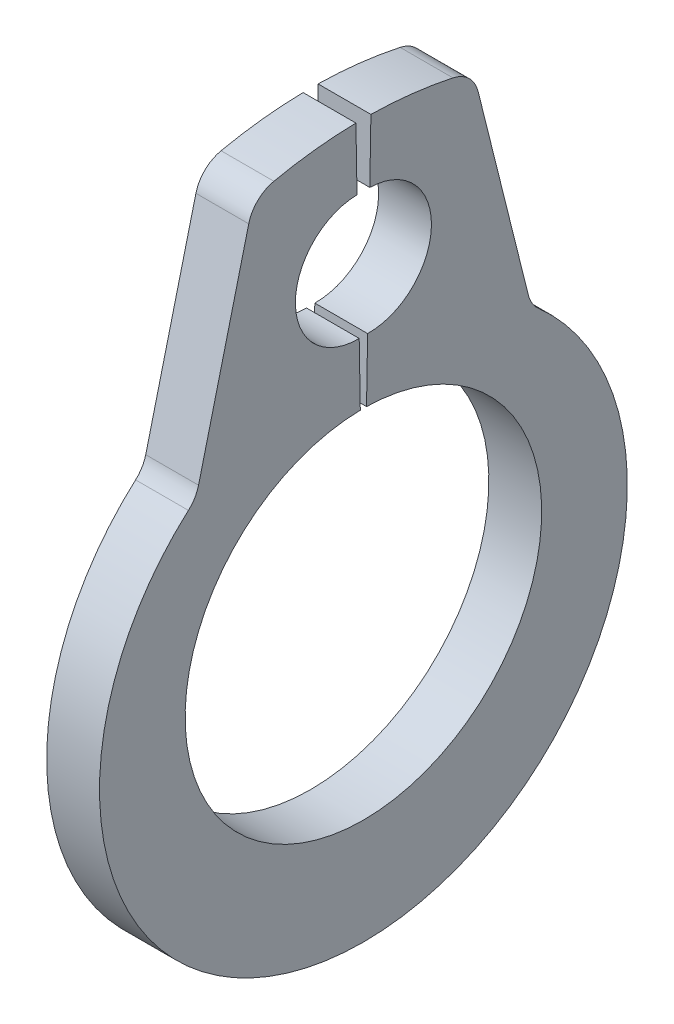
SolidWorks part; units mm, degrees
material "Cast Carbon Steel"
ref_plane "Front" through (0, 0, 0) normal (0, 0, 1) x (1, 0, 0)
ref_plane "Top" through (0, 0, 0) normal (0, 1, 0) x (1, 0, 0)
ref_plane "Right" through (0, 0, 0) normal (1, 0, 0) x (0, 0, -1)
sketch "Sketch1" plane through (0, 0, 0) normal (1, 0, 0) x (0, 0, -1)
  line L0 (0, 0) -> (0, 1.35) construction
  line L1 (-0.0236, 1.3498) -> (-0.0567, 3.2495) construction
  line L2 (-0.0567, 3.2495) -> (-0.808, 3.2364) construction
  line L3 (-0.808, 3.2364) -> (-1.2677, 1.3928) construction
  line L4 (0.0567, 3.2495) -> (0.0236, 1.3498) construction
  line L5 (0.0567, 3.2495) -> (0.808, 3.2364) construction
  line L6 (0.808, 3.2364) -> (1.2677, 1.3928) construction
  line L7 (-1.2677, 1.3928) -> (-0.9087, 0.9984) construction
  line L8 (1.2677, 1.3928) -> (0.9087, 0.9984) construction
  line L9 (0, -1.35) -> (0, -2.15) construction
  line L10 (-0.808, 3.2364) -> (-0.0236, 1.3498) construction
  line L11 (0.0236, 1.3498) -> (0.0319, 1.8247)
  line L12 (0, 1.35) -> (0, 3.25) construction
  line L13 (0.8316, 3.1418) -> (1.2677, 1.3928)
  line L14 (-0.8316, 3.1418) -> (-1.2677, 1.3928)
  line L16 (0.0484, 2.7746) -> (0.0567, 3.2495)
  line L17 (-0.0484, 2.7746) -> (-0.0567, 3.2495)
  line L18 (-0.0319, 1.8247) -> (-0.0236, 1.3498)
  circle A0 centre (0, 0) radius 1.35 construction
  arc A1 (-0.0236, 1.3498) -> (0.0236, 1.3498) centre (0, 0) ccw
  circle A2 centre (0, -0.1518) radius 1.9982 construction
  arc A3 (0.0484, 2.7746) -> (0.0319, 1.8247) centre (0.0401, 2.2996) cw
  arc A4 (-0.0319, 1.8247) -> (-0.0484, 2.7746) centre (-0.0401, 2.2996) cw
  arc A6 (-1.2677, 1.3928) -> (1.2677, 1.3928) centre (0, -0.1518) ccw
  arc A7 (0.0567, 3.2495) -> (0.8316, 3.1418) centre (0, 0) cw
  arc A8 (-0.0567, 3.2495) -> (-0.8316, 3.1418) centre (0, 0) ccw
  dimension "A" = 2.7
  dimension "Smin" = 0.5333
  dimension "D1" = 75
  dimension "Angle" = 1
  dimension "H" = 1.9
  dimension "D2" = 0.95
extrude "Extrude1" add sketch "Sketch1" along normal mid plane 0.4
fillet "Fillet1" radius 0.25 4 edges at (0, 1.3928, 1.2677) (0, 3.1418, 0.8316) (0, 3.1418, -0.8316) (0, 1.3928, -1.2677)
sketch "Sketch2" plane through (0, 0, 0) normal (0, 0, 1) x (1, 0, 0)
  line L0 (-1.25, 0) -> (3.75, 0)
  line L1 (3.75, 0) -> (3.75, -1.5)
  line L2 (-0.25, -1.5) -> (-1.15, -1.5)
  line L3 (3.75, -1.5) -> (0.25, -1.5)
  line L4 (0.25, -1.5) -> (0.25, -1.4)
  line L5 (0.25, -1.4) -> (-0.25, -1.4)
  line L6 (-0.25, -1.4) -> (-0.25, -1.5)
  line L7 (-0.25, -1.5) -> (-1.25, -1.5) construction
  line L8 (-1.25, -1.5) -> (-1.25, 0) construction
  line L9 (0, -1.4) -> (0, 0) construction
  line L10 (3.75, 0) -> (14.0551, 0) construction
  line L11 (-1.15, -1.5) -> (-1.25, -1.4)
  line L12 (-1.25, -1.4) -> (-1.25, 0)
  dimension "D2" = 5
  dimension "D3" = 1.25
  dimension "D1" = 45
revolve "Revolve1" [suppressed] add sketch "Sketch2" angle 360 about L10
equation "\"D2@Sketch2\" = \"W@Sketch2\"*10"
equation "\"D3@Sketch2\" = \"D2@Sketch2\"/4"
equation "\"Smin@Sketch1\" = \"Smax@Sketch1\"/1.5"
equation "\"D2@Sketch1\" = \"H@Sketch1\"/2"
